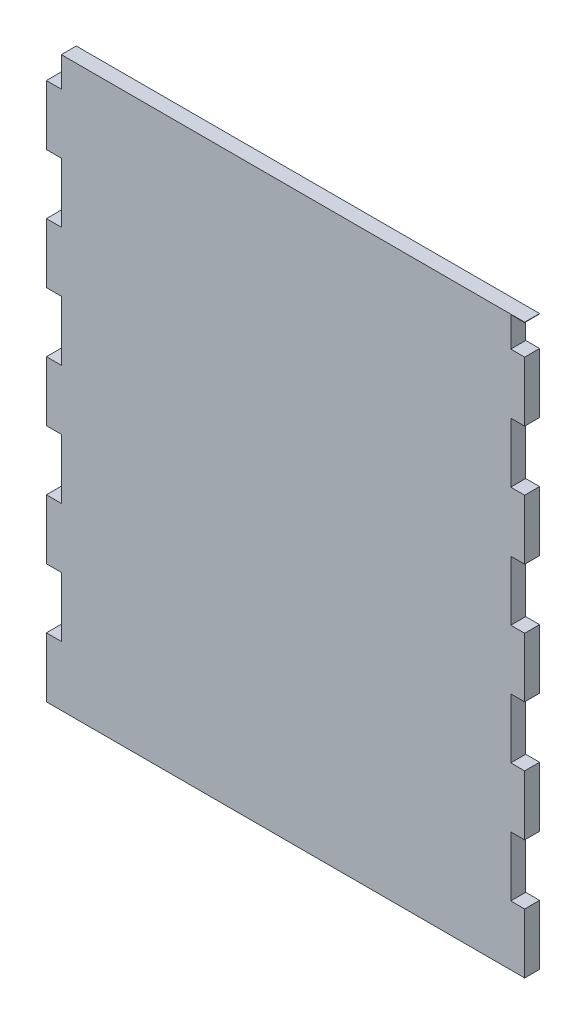
SolidWorks part; units mm, degrees
ref_plane "Front Plane" through (0, 0, 0) normal (0, 0, 1) x (1, 0, 0)
ref_plane "Top Plane" through (0, 0, 0) normal (0, 1, 0) x (1, 0, 0)
ref_plane "Right Plane" through (0, 0, 0) normal (1, 0, 0) x (0, 0, -1)
sketch "Sketch1" plane through (0, 0, 0) normal (0, 0, 1) x (1, 0, 0)
  line L1 (-202.6682, 117.9755) -> (0.5318, 117.9755)
  line L2 (-202.6682, 117.9755) -> (-202.6682, -123.3245)
  line L3 (-202.6682, -123.3245) -> (0.5318, -123.3245)
  line L4 (0.5318, 117.9755) -> (0.5318, -123.3245)
  dimension "D1" = 241.3
  dimension "D2" = 203.2
extrude "Boss-Extrude1" add sketch "Sketch1" along normal blind 6.35
sketch "Sketch2" plane through (0, 0, 6.35) normal (0, 0, 1) x (1, 0, 0)
  line L0 (-202.6682, 117.9755) -> (-202.6682, -123.3245) construction
  line L1 (-202.6682, -97.9245) -> (-196.3182, -97.9245)
  line L2 (-202.6682, -97.9245) -> (-202.6682, -72.5245)
  line L3 (-202.6682, -72.5245) -> (-196.3182, -72.5245)
  line L4 (-196.3182, -97.9245) -> (-196.3182, -72.5245)
  line L5 (-202.6682, -123.3245) -> (0.5318, -123.3245) construction
  line L6 (-202.6682, 117.9755) -> (-202.6682, -123.3245) construction
  line L7 (-202.6682, -47.1245) -> (-196.3182, -47.1245)
  line L8 (-202.6682, -47.1245) -> (-202.6682, -21.7245)
  line L9 (-202.6682, -21.7245) -> (-196.3182, -21.7245)
  line L10 (-196.3182, -47.1245) -> (-196.3182, -21.7245)
  line L11 (-202.6682, 3.6755) -> (-196.3182, 3.6755)
  line L12 (-202.6682, 3.6755) -> (-202.6682, 29.0755)
  line L13 (-202.6682, 29.0755) -> (-196.3182, 29.0755)
  line L14 (-196.3182, 3.6755) -> (-196.3182, 29.0755)
  line L15 (-202.6682, 54.4755) -> (-196.3182, 54.4755)
  line L16 (-202.6682, 54.4755) -> (-202.6682, 79.8755)
  line L17 (-202.6682, 79.8755) -> (-196.3182, 79.8755)
  line L18 (-196.3182, 54.4755) -> (-196.3182, 79.8755)
  line L19 (-202.6682, 105.2755) -> (-196.3182, 105.2755)
  line L20 (-202.6682, 105.2755) -> (-202.6682, 117.9755)
  line L21 (-202.6682, 117.9755) -> (-196.3182, 117.9755)
  line L22 (-196.3182, 105.2755) -> (-196.3182, 117.9755)
  line L23 (0.5318, 117.9755) -> (-202.6682, 117.9755) construction
  line L24 (-5.3773, -97.9245) -> (0.9727, -97.9245)
  line L25 (-5.3773, -97.9245) -> (-5.3773, -72.5245)
  line L26 (-5.3773, -72.5245) -> (0.9727, -72.5245)
  line L27 (0.9727, -97.9245) -> (0.9727, -72.5245)
  line L28 (-5.3773, -47.1245) -> (0.9727, -47.1245)
  line L29 (-5.3773, -47.1245) -> (-5.3773, -21.7245)
  line L30 (-5.3773, -21.7245) -> (0.9727, -21.7245)
  line L31 (0.9727, -47.1245) -> (0.9727, -21.7245)
  line L32 (-5.3773, 3.5082) -> (0.9727, 3.5082)
  line L33 (-5.3773, 3.5082) -> (-5.3773, 28.9082)
  line L34 (-5.3773, 28.9082) -> (0.9727, 28.9082)
  line L35 (0.9727, 3.5082) -> (0.9727, 28.9082)
  line L36 (-5.3773, 54.3082) -> (0.9727, 54.3082)
  line L37 (-5.3773, 54.3082) -> (-5.3773, 79.7082)
  line L38 (-5.3773, 79.7082) -> (0.9727, 79.7082)
  line L39 (0.9727, 54.3082) -> (0.9727, 79.7082)
  line L40 (-5.3773, 105.1082) -> (0.9727, 105.1082)
  line L41 (-5.3773, 105.1082) -> (-5.3773, 117.8082)
  line L42 (-5.3773, 117.8082) -> (0.9727, 117.8082)
  line L43 (0.9727, 105.1082) -> (0.9727, 117.8082)
  dimension "D1" = 6.35
  dimension "D2" = 25.4
  dimension "D3" = 25.4
  dimension "D4" = 25.4
  dimension "D5" = 25.4
  dimension "D6" = 6.35
  dimension "D7" = 12.7
  dimension "D8" = 25.4
  dimension "D9" = 25.4
  dimension "D10" = 25.4
  dimension "D11" = 25.4
  dimension "D12" = 25.4
  dimension "D13" = 25.4
  dimension "D14" = 25.4
  dimension "D15" = 25.4
  dimension "D16" = 6.35
  dimension "D17" = 12.7
  dimension "D18" = 25.4
  dimension "D19" = 25.4
  dimension "D20" = 25.4
  dimension "D21" = 25.4
  dimension "D22" = 25.2327
  dimension "D23" = 25.4
extrude "Cut-Extrude2" cut sketch "Sketch2" against normal blind 7.62
